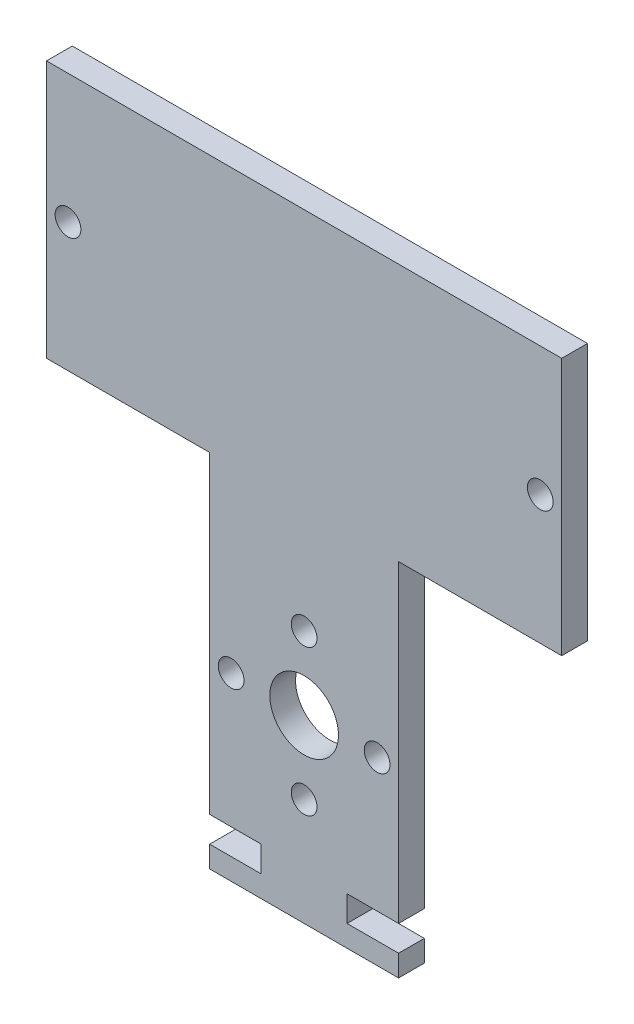
SolidWorks part; units mm, degrees
ref_plane "Front Plane" through (0, 0, 0) normal (0, 0, 1) x (1, 0, 0)
ref_plane "Top Plane" through (0, 0, 0) normal (0, 1, 0) x (1, 0, 0)
ref_plane "Right Plane" through (0, 0, 0) normal (1, 0, 0) x (0, 0, -1)
sketch "Sketch1" plane through (0, 0, 0) normal (0, 0, 1) x (1, 0, 0)
  line L16 (-11, 0) -> (-11, -15.5)
  line L17 (-11, -15.5) -> (-5, -15.5)
  line L18 (-5, -15.5) -> (-5, -18.5)
  line L19 (-5, -18.5) -> (-11, -18.5)
  line L20 (-11, -18.5) -> (-11, -21)
  line L21 (-11, -21) -> (11, -21)
  line L22 (11, -21) -> (11, -18.5)
  line L23 (11, -18.5) -> (5, -18.5)
  line L24 (5, -18.5) -> (5, -15.5)
  line L25 (5, -15.5) -> (11, -15.5)
  line L26 (11, -15.5) -> (11, 0)
  line L27 (-11, 0) -> (-11, 21)
  line L28 (-11, 21) -> (-30, 21)
  line L29 (-30, 21) -> (-30, 51)
  line L30 (-30, 51) -> (30, 51)
  line L31 (30, 51) -> (30, 21)
  line L32 (30, 21) -> (11, 21)
  line L33 (11, 21) -> (11, 0)
  circle A0 centre (0, 0) radius 11 construction
  circle A1 centre (0, 8.5) radius 1.5
  circle A2 centre (8.5, 0) radius 1.5
  circle A3 centre (0, -8.5) radius 1.5
  circle A4 centre (-8.5, 0) radius 1.5
  circle A5 centre (-27.5, 36) radius 1.5
  circle A6 centre (27.5, 36) radius 1.5
  circle A7 centre (0, 0) radius 4
  point P30 (0, 51)
  point P31 (-30, 36)
  point P36 (30, 36)
  dimension "D1" = 22
  dimension "D2" = 3
  dimension "D14" = 3
  dimension "D16" = 3
  dimension "D18" = 8
  dimension "D3" = 8.5
  dimension "D5" = 10
  dimension "D6" = 5
  dimension "D7" = 21
  dimension "D8" = 3
  dimension "D9" = 3
  dimension "D10" = 18.5
  dimension "D11" = 60
  dimension "D12" = 30
  dimension "D13" = 21
  dimension "D15" = 2.5
  dimension "D17" = 2.5
  dimension "D4" = 4
extrude "Boss-Extrude1" add sketch "Sketch1" along normal blind 3
